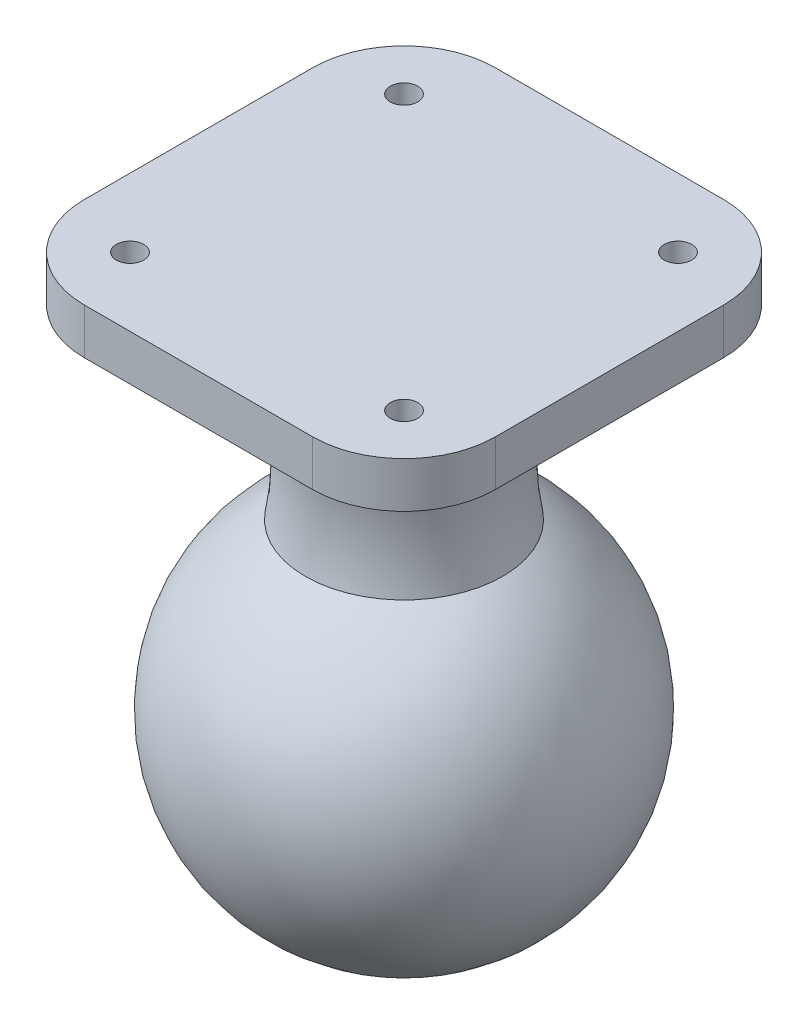
SolidWorks part; units mm, degrees
ref_plane "Front Plane" through (0, 0, 0) normal (0, 0, 1) x (1, 0, 0)
ref_plane "Top Plane" through (0, 0, 0) normal (0, 1, 0) x (1, 0, 0)
ref_plane "Right Plane" through (0, 0, 0) normal (1, 0, 0) x (0, 0, -1)
sketch "Sketch1" plane through (0, 0, 0) normal (0, 1, 0) x (1, 0, 0)
  line L0 (0, 21.0626) -> (0, -19.8901) construction
  line L1 (-21.7744, 0) -> (20.5182, 0) construction
  line L3 (12.5, -22.5) -> (-12.5, -22.5)
  line L4 (22.5, -12.5) -> (22.5, 12.5)
  line L5 (12.5, 22.5) -> (-12.5, 22.5)
  line L6 (-22.5, -12.5) -> (-22.5, 12.5)
  line L7 (22.5, -22.5) -> (-22.5, 22.5) construction
  line L8 (22.5, 22.5) -> (-22.5, -22.5) construction
  circle A1 centre (-15, 15) radius 1.5
  circle A2 centre (15, 15) radius 1.5
  circle A3 centre (15, -15) radius 1.5
  circle A4 centre (-15, -15) radius 1.5
  arc A5 (22.5, 12.5) -> (12.5, 22.5) centre (12.5, 12.5) ccw
  arc A6 (12.5, -22.5) -> (22.5, -12.5) centre (12.5, -12.5) ccw
  arc A7 (-12.5, -22.5) -> (-22.5, -12.5) centre (-12.5, -12.5) cw
  arc A8 (-12.5, 22.5) -> (-22.5, 12.5) centre (-12.5, 12.5) ccw
  point P0 (0, 0)
  dimension "D1" = 3
  dimension "D2" = 45
  dimension "D3" = 45
  dimension "D4" = 10
extrude "Boss-Extrude1" add sketch "Sketch1" along normal blind 5
sketch "Sketch5" plane through (0, 0, 0) normal (0, 0, 1) x (1, 0, 0)
  line L0 (-12.5, 0) -> (12.5, 0) construction
  line L3 (0, 0) -> (0, -30)
  line L4 (0, -30) -> (-14.4909, -30)
  line L5 (0, 0) -> (-14.4909, 0)
  line L6 (0, 6.6232) -> (0, -25.0787) construction
  line L7 (-22.5, 0) -> (-12.5, 0) construction
  line L8 (-22.5, 5) -> (-22.5, 0) construction
  arc A0 (-14.4909, 0) -> (-14.4909, -30) centre (-39.3102, -15) cw
  dimension "D3" = 29
  dimension "D1" = 30
  dimension "D5" = 0
revolve "Revolve5" add sketch "Sketch5" angle 360 about L6
sketch "Sketch6" plane through (0, 0, 0) normal (1, 0, 0) x (0, 0, -1)
  line L1 (0, -17.3238) -> (0, -59.1192)
  line L2 (0, -62.9626) -> (0, -9.2015) construction
  arc A3 (0, -17.3238) -> (0, -59.1192) centre (0, -38.2215) ccw
revolve "Revolve6" add sketch "Sketch6" angle 360 about L2
